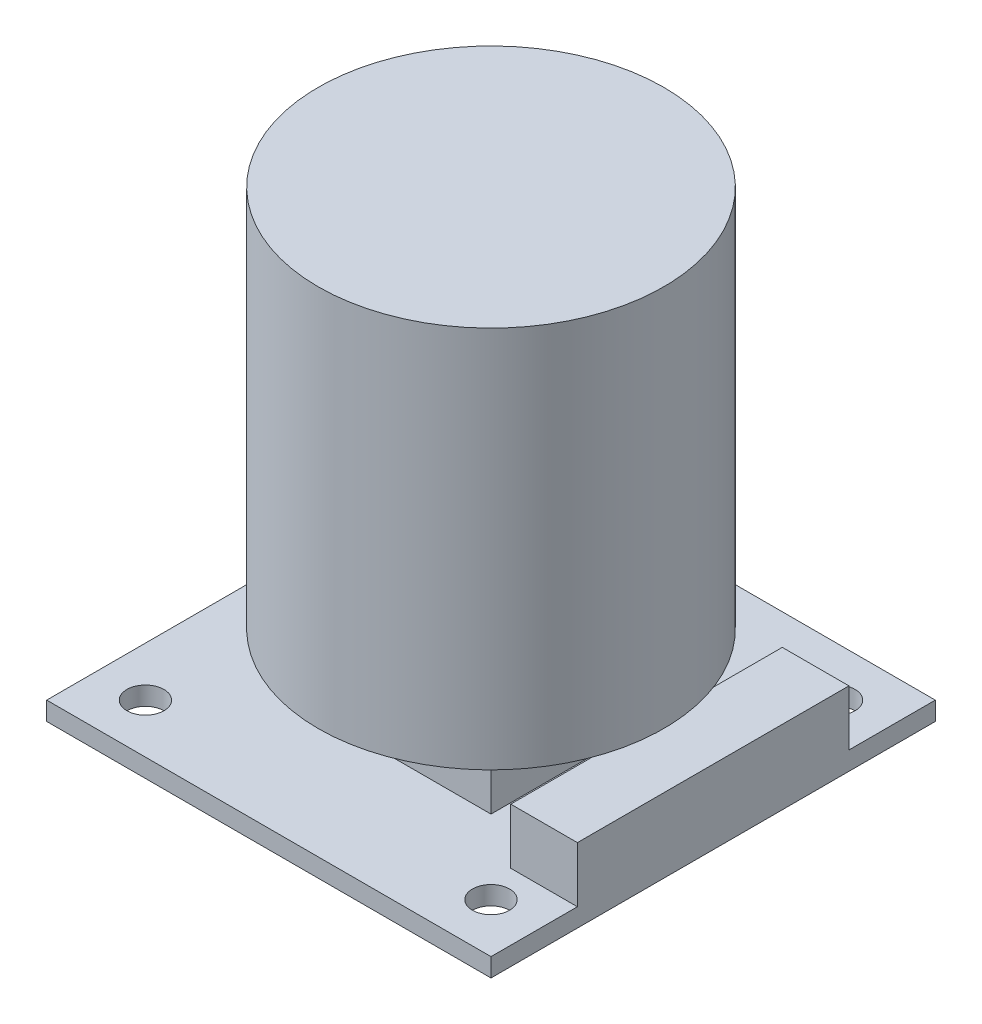
SolidWorks part; units mm, degrees
ref_plane "Front Plane" through (0, 0, 0) normal (0, 0, 1) x (1, 0, 0)
ref_plane "Top Plane" through (0, 0, 0) normal (0, 1, 0) x (1, 0, 0)
ref_plane "Right Plane" through (0, 0, 0) normal (1, 0, 0) x (0, 0, -1)
sketch "Sketch1" plane through (0, 0, 0) normal (0, 1, 0) x (1, 0, 0)
  line L1 (-18, -18) -> (18, -18)
  line L2 (-18, -18) -> (-18, 18)
  line L3 (-18, 18) -> (18, 18)
  line L4 (18, -18) -> (18, 18)
  line L5 (-18, -18) -> (18, 18) construction
  line L6 (-18, 18) -> (18, -18) construction
  point P0 (0, 0)
  dimension "D1" = 36
  dimension "D2" = 36
extrude "Boss-Extrude1" add sketch "Sketch1" along normal blind 1.5
sketch "Sketch2" plane through (0, 1.5, 0) normal (0, 1, 0) x (1, 0, 0)
  line L1 (-14, -14) -> (14, -14) construction
  line L2 (-14, -14) -> (-14, 14) construction
  line L3 (-14, 14) -> (14, 14) construction
  line L4 (14, -14) -> (14, 14) construction
  line L5 (-14, -14) -> (14, 14) construction
  line L6 (-14, 14) -> (14, -14) construction
  circle A0 centre (14, 14) radius 1.5
  circle A1 centre (14, -14) radius 1.5
  circle A2 centre (-14, -14) radius 1.5
  circle A3 centre (-14, 14) radius 1.5
  point P0 (0, 0)
  dimension "D1" = 3
  dimension "D2" = 28
  dimension "D3" = 28
extrude "Cut-Extrude1" cut sketch "Sketch2" against normal through all
sketch "Sketch5" plane through (0, 1.5, 0) normal (0, 1, 0) x (1, 0, 0)
  line L0 (18, 0) -> (-49982, 0) construction
  line L1 (18, -18) -> (18, 18) construction
  line L3 (12.6, -11) -> (18, -11)
  line L4 (12.6, -11) -> (12.6, 11)
  line L5 (12.6, 11) -> (18, 11)
  line L6 (18, -11) -> (18, 11)
  line L7 (12.6, -11) -> (18, 11) construction
  line L8 (12.6, 11) -> (18, -11) construction
  point P4 (18, 0)
  point P5 (15.3, 0)
  dimension "D1" = 5.4
  dimension "D2" = 22
extrude "Boss-Extrude4" add sketch "Sketch5" along normal blind 4.5
sketch "Sketch6" plane through (0, 1.5, 0) normal (0, 1, 0) x (1, 0, 0)
  line L1 (8, -8) -> (-8, -8)
  line L2 (8, -8) -> (8, 8)
  line L3 (8, 8) -> (-8, 8)
  line L4 (-8, -8) -> (-8, 8)
  line L5 (8, -8) -> (-8, 8) construction
  line L6 (8, 8) -> (-8, -8) construction
  point P0 (0, 0)
  dimension "D1" = 16
  dimension "D2" = 16
extrude "Boss-Extrude5" add sketch "Sketch6" along normal blind 5
sketch "Sketch7" plane through (0, 6.5, 0) normal (0, 1, 0) x (1, 0, 0)
  circle A0 centre (0, 0) radius 14
  dimension "D1" = 28
extrude "Boss-Extrude6" add sketch "Sketch7" along normal blind 31
